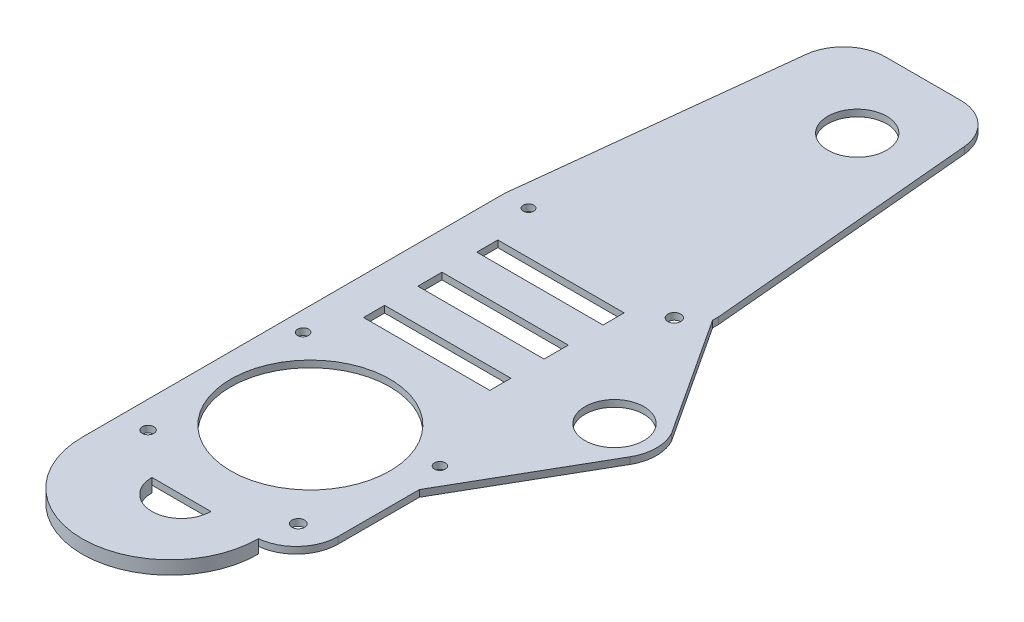
SolidWorks part; units mm, degrees
ref_plane "Front" through (0, 0, 0) normal (0, 0, 1) x (1, 0, 0)
ref_plane "Top" through (0, 0, 0) normal (0, 1, 0) x (1, 0, 0)
ref_plane "Right" through (0, 0, 0) normal (1, 0, 0) x (0, 0, -1)
sketch "Sketch1" plane through (0, 0, 0) normal (0, 1, 0) x (1, 0, 0)
  line L0 (10.4543, 228.6) -> (0, 135.3627)
  line L1 (0, 0) -> (50.8, 0)
  line L2 (0, 0) -> (0, 228.6)
  line L3 (0, 228.6) -> (50.8, 228.6)
  line L4 (50.8, 0) -> (50.8, 228.6)
  line L5 (42.3273, 228.6) -> (50.8, 135.3627)
  line L8 (50.8, 0) -> (24.327, 0)
  line L9 (50.8, 0) -> (50.8, -15)
  line L16 (50.8, 120.6192) -> (50.8, 104.4882)
  line L18 (50.8, 64.8791) -> (50.8, 87.4235)
  circle A12 centre (60.4, 101.001) radius 10
  circle A13 centre (29.5042, 189.5572) radius 7
  circle A15 centre (24.1018, 108.7849) radius 2.875
  dimension "D3" = 20
  dimension "D5" = 15
  dimension "D6" = 14
  dimension "D7" = 119.8151
  dimension "D1" = 50.8
  dimension "D2" = 228.6
extrude "Boss-Extrude1" add sketch "Sketch1" along normal blind 24.5875 contours L1 L4 L3 L0 L2
sketch "Sketch4" plane through (0, 0, -228.6) normal (0, 0, -1) x (-1, 0, 0)
  line L1 (-61.3109, 11.9192) -> (4.9615, 11.9192)
  line L2 (-61.3109, 11.9192) -> (-61.3109, -15.8811)
  line L3 (-61.3109, -15.8811) -> (4.9615, -15.8811)
  line L4 (4.9615, 11.9192) -> (4.9615, -15.8811)
extrude "Cut-Extrude2" cut sketch "Sketch4" against normal blind 20
fillet "Fillet3" radius 10 1 edges at (44.1447, 5.9596, -208.6)
fillet "Fillet4" radius 10 3 edges at (50.8, 12.2938, 0) (0, 12.2938, 0) (8.2118, 5.9596, -208.6)
sketch "Sketch6" plane through (0, 24.5875, 0) normal (0, 1, 0) x (1, 0, 0)
  line L0 (68.8909, 106.2834) -> (50.8, 135.3627)
  line L1 (50.8, 135.3627) -> (50.8, 103.801)
  line L2 (69.2582, 96.3607) -> (50.8, 61.1242)
  line L3 (50.8, 10) -> (50.8, 98.201) construction
  line L4 (50.8, 61.1242) -> (50.8, 96.3607)
  line L5 (50.8, 96.3607) -> (50.8, 98.201)
  circle A0 centre (60.4, 101.001) radius 10
extrude "Boss-Extrude3" add sketch "Sketch6" against normal blind 1.5875
sketch "Sketch7" plane through (0, 24.5875, 0) normal (0, 1, 0) x (1, 0, 0)
  circle A0 centre (60.4, 101.001) radius 7
  dimension "D1" = 14
extrude "Cut-Extrude3" cut sketch "Sketch7" against normal blind 1.5875
sketch "Sketch8" plane through (0, 24.5875, 0) normal (0, 1, 0) x (1, 0, 0)
  line L0 (35.0123, 208.6) -> (17.1532, 208.6) construction
  line L1 (9.492, 121.9099) -> (34.9257, 121.9099)
  line L2 (9.492, 121.9099) -> (9.492, 115.9099)
  line L3 (9.492, 115.9099) -> (34.9257, 115.9099)
  line L4 (34.9257, 121.9099) -> (34.9257, 115.9099)
  line L5 (9.492, 134.7849) -> (34.9257, 134.7849)
  line L6 (9.492, 134.7849) -> (9.492, 129.7849)
  line L7 (9.492, 129.7849) -> (34.9257, 129.7849)
  line L8 (34.9257, 134.7849) -> (34.9257, 129.7849)
  line L9 (9.492, 107.7849) -> (34.9257, 107.7849)
  line L10 (9.492, 107.7849) -> (9.492, 102.7849)
  line L11 (9.492, 102.7849) -> (34.9257, 102.7849)
  line L12 (34.9257, 107.7849) -> (34.9257, 102.7849)
  circle A0 centre (9.492, 118.9099) radius 3
  circle A1 centre (34.9257, 118.9099) radius 3
  circle A2 centre (23.3804, 122.2849) radius 2.5
  circle A4 centre (24.1018, 108.7849) radius 2.875 construction
  circle A5 centre (9.492, 132.2849) radius 2.5
  circle A6 centre (34.9257, 132.2849) radius 2.5
  circle A7 centre (24.29, 95.2849) radius 2.5
  circle A8 centre (24.1018, 108.7849) radius 2.875 construction
  circle A9 centre (9.492, 105.2849) radius 2.5
  circle A10 centre (34.9257, 105.2849) radius 2.5
  circle A11 centre (24.5838, 64.5939) radius 18.9
  circle M15 centre (24.1018, 108.7849) radius 2.875
  dimension "D1" = 13.5
  dimension "D2" = 13.5
  dimension "D3" = 73.8151
extrude "Cut-Extrude4" cut sketch "Sketch8" against normal blind 10 contours A1 L1 A0 L3 M15 | L2 A0 | L2 A0 | M15 | L4 A1 | L4 A1 | A5 L7 A2 L5 | A9 L11 A7 L9 | A10 L9 A7 L11 | A7 | A6
sketch "Sketch9" plane through (0, 0, 0) normal (0, -1, 0) x (1, 0, 0)
  line L1 (134.4567, -306.3857) -> (-94.6503, -306.3857)
  line L2 (134.4567, -306.3857) -> (134.4567, 54.8813)
  line L3 (134.4567, 54.8813) -> (-94.6503, 54.8813)
  line L4 (-94.6503, -306.3857) -> (-94.6503, 54.8813)
  circle A0 centre (6.3356, -44.2888) radius 1.3882
  circle A1 centre (43.4477, -42.8684) radius 1.4834
  circle A2 centre (4.6595, -82.7932) radius 1.3149
  circle A3 centre (48.401, -71.551) radius 1.2486
  circle A4 centre (5.8847, -135.1031) radius 1.2556
  circle A5 centre (45.7477, -129.8635) radius 1.5391
extrude "Cut-Extrude5" cut sketch "Sketch9" against normal blind 13
sketch "Sketch10" plane through (0, 24.5875, 0) normal (0, 1, 0) x (1, 0, 0)
  line L1 (8.7856, 124.9149) -> (38.774, 124.9149)
  line L2 (8.7856, 124.9149) -> (8.7856, 119.9149)
  line L3 (8.7856, 119.9149) -> (38.774, 119.9149)
  line L4 (38.774, 124.9149) -> (38.774, 119.9149)
  line L5 (8.7856, 111.6599) -> (38.774, 111.6599)
  line L6 (8.7856, 111.6599) -> (8.7856, 105.9099)
  line L7 (8.7856, 105.9099) -> (38.774, 105.9099)
  line L8 (38.774, 111.6599) -> (38.774, 105.9099)
  line L9 (8.7856, 98.0289) -> (38.774, 98.0289)
  line L10 (8.7856, 98.0289) -> (8.7856, 93.0289)
  line L11 (8.7856, 93.0289) -> (38.774, 93.0289)
  line L12 (38.774, 98.0289) -> (38.774, 93.0289)
  circle A0 centre (23.841, 122.4149) radius 2.5
  circle A1 centre (24.1018, 108.7849) radius 2.875 construction
  circle A2 centre (23.841, 95.5289) radius 2.5
  circle M1 centre (9.492, 118.9099) radius 3
  dimension "D1" = 13.63
extrude "Cut-Extrude6" cut sketch "Sketch10" against normal blind 22 contours A0 L1 L2 L3 M1 | A0 L3 L4 L1 | A0 | L8 L5 L6 L7 | A2 L9 L10 L11 | A2 L11 L12 L9 | A2 | L2 L3 M1
sketch "Sketch11" plane through (0, 24.5875, 0) normal (0, 1, 0) x (1, 0, 0)
  circle A0 centre (8.5355, 118.295) radius 5.2367
extrude "Cut-Extrude7" cut sketch "Sketch11" against normal blind 10
sketch "Sketch12" plane through (0, 14.5875, 0) normal (0, 1, 0) x (1, 0, 0)
  line L0 (50.8, 133.9005) -> (69.1954, 105.7592)
  line L1 (50.8, 103.801) -> (50.8, 135.3627) construction
  line L2 (69.0677, 96.0139) -> (50.8, 64.2642)
  line L3 (50.8, 10) -> (50.8, 98.201) construction
  line L4 (50.8, 64.2642) -> (50.8, 98.201)
  line L5 (50.8, 133.9005) -> (50.8, 103.801)
  circle A0 centre (60.4, 101.001) radius 10
  line M24 (50.8, 10) -> (50.8, 98.201)
  arc M25 (50.8, 98.201) -> (50.8, 103.801) centre (60.4, 101.001) cw
  line M26 (50.8, 103.801) -> (50.8, 135.3627)
extrude "Boss-Extrude4" add sketch "Sketch12" against normal blind 1.59 contours A0 L0 M26 | L0 A0 M25 | A0 L2 M24
sketch "Sketch13" plane through (0, 14.5875, 0) normal (0, 1, 0) x (1, 0, 0)
  circle A0 centre (60.4, 101.001) radius 7
extrude "Cut-Extrude8" cut sketch "Sketch13" against normal blind 41
sketch "Sketch14" plane through (0, 0, -228.6) normal (0, 0, -1) x (-1, 0, 0)
  line L1 (-2.551, 39.1752) -> (-64.0429, 39.1752)
  line L2 (-2.551, 39.1752) -> (-2.551, 3.5877)
  line L3 (-2.551, 3.5877) -> (-64.0429, 3.5877)
  line L4 (-64.0429, 39.1752) -> (-64.0429, 3.5877)
extrude "Cut-Extrude9" cut sketch "Sketch14" against normal blind 20
fillet "Fillet5" radius 10 2 edges at (8.2118, 13.7938, -208.6) (44.1447, 13.7938, -208.6)
sketch "Sketch16" plane through (0, 0, 0) normal (0, 0, 1) x (1, 0, 0)
  line L1 (-74.9257, 20.893) -> (88.7974, 20.893)
  line L2 (-74.9257, 20.893) -> (-74.9257, -1.979)
  line L3 (-74.9257, -1.979) -> (88.7974, -1.979)
  line L4 (88.7974, 20.893) -> (88.7974, -1.979)
extrude "Cut-Extrude11" cut sketch "Sketch16" against normal blind 35
fillet "Fillet6" radius 10 2 edges at (50.8, 13.7938, -35) (0, 13.7938, -35)
sketch "Sketch17" plane through (0, 0, 0) normal (0, -1, 0) x (1, 0, 0)
  circle A0 centre (45.7477, -129.8635) radius 1.5391
  circle A1 centre (5.8847, -135.1031) radius 1.2556
  circle A2 centre (48.401, -71.551) radius 1.3
  circle A3 centre (4.6595, -82.7932) radius 1.3149
  circle A4 centre (6.3356, -44.2888) radius 1.3882
  circle A5 centre (43.4477, -42.8684) radius 1.5
extrude "Cut-Extrude12" cut sketch "Sketch17" against normal blind 42
sketch "Sketch18" plane through (0, 24.5875, 0) normal (0, 1, 0) x (1, 0, 0)
  circle A0 centre (24.5838, 64.5939) radius 18.9
extrude "Cut-Extrude13" cut sketch "Sketch18" against normal blind 30
sketch "Sketch19" plane through (0, 14.5875, 0) normal (0, 1, 0) x (1, 0, 0)
  line L0 (0, 135.3627) -> (0, 45) construction
  line L1 (0, 65) -> (-40, 65)
  line L2 (0, 65) -> (0, 35)
  line L3 (0, 35) -> (-40, 35)
  line L4 (-40, 65) -> (-40, 35)
  line L5 (40.8, 35) -> (10, 35) construction
  line L6 (0, 35) -> (15.576, 35)
  line L7 (10, 35) -> (40.8, 35) construction
  line L8 (-40, 35) -> (15.576, 9.2927)
  line L9 (15.576, 9.2927) -> (50.8407, 10.2732)
  line L10 (50.8407, 10.2732) -> (41.7914, 35.0493)
  circle A0 centre (23.5462, 35) radius 7
  arc A1 (40.8, 35) -> (50.8, 45) centre (40.8, 45) ccw construction
  arc A2 (0, 35) -> (41.7914, 35.0493) centre (20.8957, 35) ccw
  line M25 (10, 35) -> (40.8, 35)
  arc M26 (40.8, 35) -> (50.8, 45) centre (40.8, 45) ccw
  arc M38 (0, 45) -> (10, 35) centre (10, 45) ccw
  dimension "D1" = 14
  dimension "D2" = 0
  dimension "D3" = 30
  dimension "D6" = 40
extrude "Boss-Extrude5" add sketch "Sketch19" against normal blind 3.175 contours L2 L6 M38 | L9 L10 L6 L3 L8 A0 M26 M25
equation "\"7i\"=101.6"
